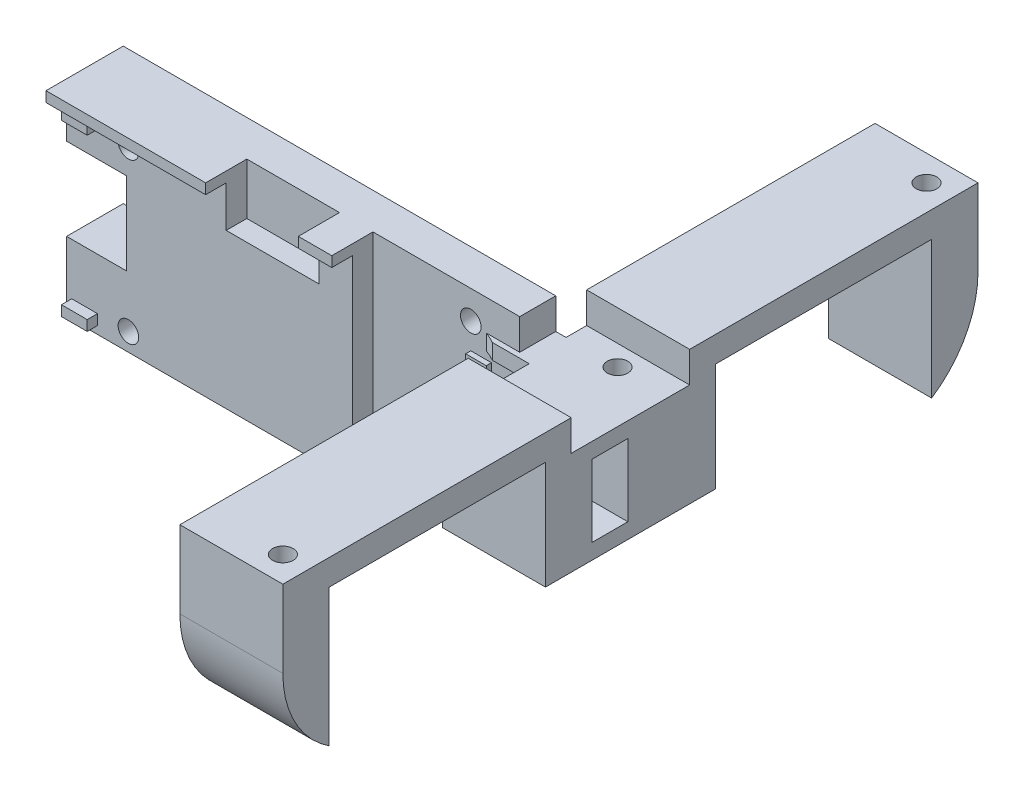
SolidWorks part; units mm, degrees
material "ABS"
ref_plane "Front Plane" through (0, 0, 0) normal (0, 0, 1) x (1, 0, 0)
ref_plane "Top Plane" through (0, 0, 0) normal (0, 1, 0) x (1, 0, 0)
ref_plane "Right Plane" through (0, 0, 0) normal (1, 0, 0) x (0, 0, -1)
sketch "Sketch1" plane through (0, 0, 0) normal (0, 1, 0) x (1, 0, 0)
  line L1 (-40.3176, 43.2333) -> (45.6824, 43.2333)
  line L2 (45.6824, 43.2333) -> (45.6824, -16.7667)
  line L3 (45.6824, -16.7667) -> (65.6824, -16.7667)
  line L4 (65.6824, -16.7667) -> (65.6824, 118.2333)
  line L7 (-40.3176, 43.2333) -> (-40.3176, 58.2333)
  line L8 (-40.3176, 58.2333) -> (45.6824, 58.2333)
  line L9 (45.6824, 58.2333) -> (45.6824, 118.2333)
  line L10 (45.6824, 118.2333) -> (65.6824, 118.2333)
  dimension "D1" = 20
  dimension "D2" = 60
  dimension "D3" = 86
  dimension "D4" = 15
  dimension "D5" = 60
  dimension "D6" = 20
extrude "Boss-Extrude1" add sketch "Sketch1" along normal blind 35
sketch "Sketch2" plane through (65.6824, 0, 0) normal (1, 0, 0) x (0, 0, -1)
  line L1 (-7.7667, 30) -> (34.2333, 30)
  line L2 (-7.7667, 30) -> (-7.7667, 9)
  line L3 (-7.7667, 9) -> (34.2333, 9)
  line L4 (34.2333, 30) -> (34.2333, 9)
  line L5 (-16.7667, 35) -> (-16.7667, 0) construction
  line L6 (50.7333, 24.6294) -> (50.7333, 59.3446) construction
  line L7 (-16.7667, 0) -> (118.2333, 0) construction
  line L9 (109.2333, 9) -> (67.2333, 9)
  line L10 (109.2333, 30) -> (109.2333, 9)
  line L11 (109.2333, 30) -> (67.2333, 30)
  line L12 (67.2333, 30) -> (67.2333, 9)
  dimension "D1" = 21
  dimension "D2" = 42
  dimension "D3" = 9
  dimension "D4" = 9
  dimension "D5" = 7.5
extrude "Cut-Extrude1" cut sketch "Sketch2" against normal up to next
sketch "Sketch3" plane through (45.6824, 0, 0) normal (-1, 0, 0) x (0, 0, 1)
  line L0 (7.7667, 9) -> (7.7667, 30) construction
  line L1 (-34.2333, 9) -> (7.7667, 9) construction
  line L2 (-50.7333, 32.1987) -> (-50.7333, 60.1119) construction
  line L3 (-43.2333, 35) -> (-43.2333, 0) construction
  circle A0 centre (11.2667, 24.75) radius 2
  circle A1 centre (11.2667, 15.25) radius 2
  circle A2 centre (-37.7333, 24.75) radius 2
  circle A3 centre (-37.7333, 15.25) radius 2
  circle A4 centre (-112.7333, 24.75) radius 2
  circle A5 centre (-112.7333, 15.25) radius 2
  circle A6 centre (-63.7333, 15.25) radius 2
  circle A7 centre (-63.7333, 24.75) radius 2
  dimension "D1" = 4
  dimension "D2" = 49
  dimension "D3" = 9.5
  dimension "D4" = 3.5
  dimension "D5" = 6.25
  dimension "D6" = 7.5
extrude "Cut-Extrude2" cut sketch "Sketch3" against normal blind 10
fillet "Fillet1" radius 20 2 edges at (55.6824, 0, 16.7667) (55.6824, 0, -118.2333)
sketch "Sketch6" plane through (65.6824, 0, 0) normal (1, 0, 0) x (0, 0, -1)
  line L0 (34.2333, 9) -> (34.2333, 30) construction
  line L1 (-7.7667, 9) -> (34.2333, 9)
  line L2 (-7.7667, 9) -> (-7.7667, 0)
  line L3 (-7.7667, 0) -> (34.2333, 0)
  line L4 (34.2333, 9) -> (34.2333, 0)
  line L5 (3.2333, 0) -> (98.2333, 0) construction
  line L6 (50.7333, 24.0053) -> (50.7333, 51.0852) construction
  line L7 (67.2333, 9) -> (67.2333, 0)
  line L8 (109.2333, 9) -> (67.2333, 9)
  line L9 (109.2333, 0) -> (67.2333, 0)
  line L10 (109.2333, 9) -> (109.2333, 0)
  dimension "D1" = 7.5
extrude "Cut-Extrude5" cut sketch "Sketch6" against normal up to next
sketch "Sketch8" plane through (0, 0, 0) normal (0, -1, 0) x (1, 0, 0)
  line L1 (45.6824, -67.2333) -> (45.6824, -58.2333) construction
  line L2 (45.6824, -67.2333) -> (65.6824, -67.2333) construction
  line L3 (65.6824, -34.2333) -> (65.6824, -67.2333) construction
  line L4 (45.6824, -34.2333) -> (65.6824, -34.2333) construction
  line L5 (45.6824, -43.2333) -> (45.6824, -34.2333) construction
  line L9 (45.6824, -67.2333) -> (45.6824, -58.2333)
  line L10 (45.6824, -67.2333) -> (65.6824, -67.2333)
  line L11 (65.6824, -34.2333) -> (65.6824, -67.2333)
  line L12 (45.6824, -34.2333) -> (65.6824, -34.2333)
  line L13 (45.6824, -43.2333) -> (45.6824, -34.2333)
  line L16 (45.6824, -43.2333) -> (25.6824, -43.2333)
  line L17 (-40.3176, -43.2333) -> (45.6824, -43.2333) construction
  line L18 (25.6824, -43.2333) -> (25.6824, -58.2333)
  line L19 (45.6824, -58.2333) -> (-40.3176, -58.2333) construction
  line L20 (25.6824, -58.2333) -> (45.6824, -58.2333)
  dimension "D1" = 20
extrude "Cut-Extrude7" cut sketch "Sketch8" against normal blind 9
sketch "Sketch9" plane through (0, 9, 0) normal (0, -1, 0) x (1, 0, 0)
  line L1 (65.6824, -34.2333) -> (45.6824, -34.2333) construction
  line L2 (65.6824, -67.2333) -> (65.6824, -34.2333) construction
  line L3 (45.6824, -67.2333) -> (65.6824, -67.2333) construction
  circle A0 centre (55.6824, -42.2333) radius 2
  circle A1 centre (55.6824, -59.2333) radius 2
  dimension "D4" = 10
  dimension "D5" = 8
  dimension "D6" = 8
extrude "Cut-Extrude8" cut sketch "Sketch9" against normal blind 10
sketch "Sketch10" plane through (0, 35, 0) normal (0, 1, 0) x (1, 0, 0)
  line L0 (45.6824, 62.2333) -> (65.6824, 62.2333)
  line L1 (45.6824, 118.2333) -> (45.6824, 58.2333) construction
  line L2 (65.6824, -16.7667) -> (65.6824, 118.2333) construction
  line L3 (65.6824, 62.2333) -> (65.6824, 39.2333)
  line L4 (65.6824, 39.2333) -> (45.6824, 39.2333)
  line L5 (45.6824, 43.2333) -> (45.6824, -16.7667) construction
  line L7 (45.6824, 39.2333) -> (45.6824, 43.2333)
  line L8 (45.6824, 43.2333) -> (43.6824, 43.2333)
  line L9 (-40.3176, 43.2333) -> (45.6824, 43.2333) construction
  line L10 (43.6824, 43.2333) -> (43.6824, 58.2333)
  line L11 (45.6824, 58.2333) -> (-40.3176, 58.2333) construction
  line L12 (43.6824, 58.2333) -> (45.6824, 58.2333)
  line L13 (45.6824, 58.2333) -> (45.6824, 62.2333)
  dimension "D1" = 5
  dimension "D2" = 5
  dimension "D3" = 2
extrude "Cut-Extrude9" cut sketch "Sketch10" against normal blind 6
sketch "Sketch11" plane through (0, 29, 0) normal (0, 1, 0) x (1, 0, 0)
  line L0 (45.6824, 62.2333) -> (45.6824, 58.2333) construction
  circle A0 centre (55.6824, 58.2333) radius 2
  circle A1 centre (55.6824, 43.2333) radius 2
  dimension "D1" = 4
  dimension "D2" = 10
  dimension "D5" = 0
extrude "Cut-Extrude10" cut sketch "Sketch11" against normal blind 9
sketch "Sketch12" plane through (0, 35, 0) normal (0, 1, 0) x (1, 0, 0)
  line L0 (65.6824, 118.2333) -> (45.6824, 118.2333) construction
  line L1 (45.6824, -16.7667) -> (65.6824, -16.7667) construction
  line L2 (65.6824, -16.7667) -> (65.6824, 39.2333) construction
  line L3 (65.6824, 62.2333) -> (65.6824, 118.2333) construction
  circle A0 centre (60.6824, -11.7667) radius 2
  circle A1 centre (60.6824, 113.2333) radius 2
  dimension "D2" = 4
  dimension "D1" = 5
  dimension "D3" = 5
  dimension "D4" = 5
  dimension "D5" = 5
extrude "Cut-Extrude11" cut sketch "Sketch12" against normal blind 10
sketch "Sketch14" plane through (0, 0, -43.2333) normal (0, 0, 1) x (1, 0, 0)
  line L0 (-40.3176, 35) -> (-40.3176, 0) construction
  line L1 (-40.3176, 33) -> (44.6824, 33)
  line L2 (-40.3176, 33) -> (-40.3176, 0)
  line L3 (-40.3176, 0) -> (44.6824, 0)
  line L4 (44.6824, 33) -> (44.6824, 0)
  line L5 (-40.3176, 0) -> (25.6824, 0) construction
  line L7 (-40.3176, 35) -> (43.6824, 35) construction
  dimension "D1" = 85
  dimension "D2" = 2
extrude "Cut-Extrude13" cut sketch "Sketch14" against normal blind 4
sketch "Sketch15" plane through (0, 0, -47.2333) normal (0, 0, 1) x (1, 0, 0)
  line L1 (15.6824, 20) -> (43.6824, 20)
  line L3 (15.6824, 0) -> (43.6824, 0)
  line L4 (43.6824, 20) -> (43.6824, 0)
  line L5 (43.6824, 29) -> (43.6824, 33) construction
  line L6 (-40.3176, 0) -> (25.6824, 0) construction
  line L13 (15.6824, 20) -> (15.6824, 0)
  line L14 (-40.3176, 33) -> (-40.3176, 0) construction
  point P0 (14.6824, 18.5247)
  point P7 (14.6824, 8)
  point P10 (18.6824, 8)
  point P11 (15.265, 8)
  dimension "D1" = 20
  dimension "D3" = 0
  dimension "D5" = 56
extrude "Cut-Extrude14" cut sketch "Sketch15" against normal blind 4
sketch "Sketch16" plane through (0, 0, 0) normal (0, -1, 0) x (1, 0, 0)
  line L0 (25.6824, -58.2333) -> (-40.3176, -58.2333) construction
  line L1 (-40.3176, -47.2333) -> (39.6824, -47.2333)
  line L2 (-40.3176, -47.2333) -> (-40.3176, -58.2333)
  line L3 (-40.3176, -58.2333) -> (39.6824, -58.2333)
  line L4 (39.6824, -47.2333) -> (39.6824, -58.2333)
  dimension "D1" = 80
extrude "Boss-Extrude2" add sketch "Sketch16" along normal blind 5 and the other way up to surface (9 mm away) other way up to face at (45.1824, 9, -50.2333)
sketch "Sketch13" plane through (0, 0, -43.2333) normal (0, 0, 1) x (1, 0, 0)
  line L1 (-38.3176, 32) -> (36.6824, 32) construction
  line L2 (-38.3176, 32) -> (-38.3176, -4) construction
  line L3 (-38.3176, -4) -> (36.6824, -4) construction
  line L4 (36.6824, 32) -> (36.6824, -4) construction
  line L5 (-40.3176, 33) -> (-40.3176, -5) construction
  line L6 (-40.3176, 35) -> (43.6824, 35) construction
  circle A0 centre (-28.3176, 29.5) radius 2
  circle A1 centre (34.1824, 29.5) radius 2
  circle A2 centre (34.1824, -1.5) radius 2
  circle A3 centre (-28.3176, -1.5) radius 2
  dimension "D3" = 4
  dimension "D1" = 31
  dimension "D2" = 62.5
  dimension "D4" = 75
  dimension "D5" = 36
  dimension "D6" = 2.5
  dimension "D7" = 10
  dimension "D8" = 2
  dimension "D9" = 5.5
extrude "Cut-Extrude12" cut sketch "Sketch13" against normal blind 12
fillet "Fillet2" radius 2 1 edges at (39.6824, -5, -52.7333)
sketch "Sketch17" plane through (0, 0, -43.2333) normal (0, 0, 1) x (1, 0, 0)
  line L1 (43.6824, -5) -> (15.1824, -5)
  line L2 (43.6824, -5) -> (43.6824, 35)
  line L4 (15.1824, -5) -> (15.1824, 35)
  line L5 (-40.3176, 35) -> (43.6824, 35) construction
  line L7 (-9.3176, 35) -> (8.6824, 35)
  line L8 (-9.3176, 35) -> (-9.3176, 25)
  line L9 (-9.3176, 25) -> (8.6824, 25)
  line L10 (8.6824, 35) -> (8.6824, 25)
  line L11 (15.1824, 35) -> (43.6824, 35)
  circle A1 centre (-28.3176, 29.5) radius 2 construction
  point P4 (0, 0)
  point P10 (0, 0)
  point P11 (43.6824, 35)
  point P17 (43.097, 35)
  dimension "D3" = 19
  dimension "D2" = 6.5
  dimension "D4" = 18
  dimension "D5" = 10
  dimension "D6" = 40
extrude "Cut-Extrude15" cut sketch "Sketch17" against normal blind 8
sketch "Sketch20" plane through (0, 0, -47.2333) normal (0, 0, 1) x (1, 0, 0)
  line L0 (-40.3176, 33) -> (-40.3176, -5) construction
  line L1 (-40.3176, 24.5) -> (-32.3176, 24.5)
  line L2 (-40.3176, 24.5) -> (-40.3176, 8.5)
  line L3 (-40.3176, 8.5) -> (-32.3176, 8.5)
  line L4 (-32.3176, 24.5) -> (-32.3176, 8.5)
  circle A0 centre (-28.3176, 29.5) radius 2 construction
  dimension "D1" = 8
  dimension "D2" = 16
  dimension "D3" = 5
extrude "Cut-Extrude18" cut sketch "Sketch20" against normal up to next
sketch "Sketch7" plane through (-40.3176, 0, 0) normal (-1, 0, 0) x (0, 0, 1)
  line L1 (-47.2333, -5) -> (-58.2333, -5) construction
  line L2 (-58.2333, 35) -> (-43.2333, 35) construction
  line L3 (-43.2333, 35) -> (-43.2333, 33) construction
  circle A0 centre (-50.7333, 28.5) radius 2
  circle A1 centre (-50.7333, 5) radius 2
  dimension "D1" = 4
  dimension "D2" = 10
  dimension "D4" = 6.5
  dimension "D5" = 7.5
extrude "Cut-Extrude6" cut sketch "Sketch7" against normal blind 13
chamfer "Chamfer1" distance 10 angle 20 1 edges at (-32.3176, 16.5, -47.2333)
sketch "Sketch21" plane through (0, 0, -47.2333) normal (0, 0, 1) x (1, 0, 0)
  line L0 (-38.3176, 32) -> (36.6824, 32) construction
  line L1 (-38.3176, 32) -> (-38.3176, -4) construction
  line L2 (-38.3176, -4) -> (36.6824, -4) construction
  line L3 (36.6824, 32) -> (36.6824, -4) construction
  line L5 (33.1824, 26.5) -> (39.1824, 26.5) construction
  line L6 (33.1824, 26.5) -> (33.1824, 14) construction
  line L7 (33.1824, 14) -> (39.1824, 14)
  line L8 (39.1824, 26.5) -> (39.1824, 14) construction
  line L9 (32.6824, 13) -> (37.6824, 13) construction
  line L10 (32.6824, 13) -> (32.6824, 3) construction
  line L11 (32.6824, 3) -> (37.6824, 3) construction
  line L12 (37.6824, 13) -> (37.6824, 3) construction
  circle A0 centre (-28.3176, 29.5) radius 2
  circle A1 centre (34.1824, 29.5) radius 2
  circle A2 centre (34.1824, -1.5) radius 2
  circle A3 centre (-28.3176, -1.5) radius 2
  dimension "D3" = 4
  dimension "D1" = 31
  dimension "D2" = 62.5
  dimension "D4" = 75
  dimension "D5" = 36
  dimension "D6" = 2.5
  dimension "D7" = 10
  dimension "D8" = 12.5
  dimension "D9" = 6
  dimension "D10" = 3.5
  dimension "D11" = 5.5
  dimension "D12" = 5
  dimension "D13" = 10
  dimension "D14" = 7
  dimension "D15" = 1
sketch "Sketch22" plane through (65.6824, 0, 0) normal (1, 0, 0) x (0, 0, -1)
  line L0 (39.2333, 29) -> (62.2333, 29) construction
  line L1 (43.2333, 26) -> (50.2333, 26)
  line L2 (43.2333, 26) -> (43.2333, 12)
  line L3 (43.2333, 12) -> (50.2333, 12)
  line L4 (50.2333, 26) -> (50.2333, 12)
  line L5 (39.2333, 29) -> (39.2333, 35) construction
  dimension "D1" = 14
  dimension "D2" = 3
  dimension "D3" = 4
  dimension "D4" = 7
extrude "Cut-Extrude19" cut sketch "Sketch22" against normal up to next
sketch "Sketch24" plane through (0, 29, 0) normal (0, 1, 0) x (1, 0, 0)
  line L0 (43.6824, 51.2333) -> (15.1824, 51.2333) construction
  line L1 (45.6824, 39.2333) -> (45.6824, -16.7667) construction
  line L2 (43.6824, 51.2333) -> (43.6824, 47.2333) construction
  line L3 (37.1824, 51.2333) -> (45.6824, 51.2333)
  line L4 (45.6824, 51.2333) -> (45.6824, 39.2333)
  arc A0 (37.1824, 51.2333) -> (45.6824, 39.2333) centre (32.9618, 39.2333) cw
  dimension "D1" = 6.5
extrude "Boss-Extrude4" add sketch "Sketch24" against normal up to surface (3 mm away) up to face at (51.6824, 26, -45.8999)
sketch "Sketch25" plane through (0, 9, 0) normal (0, -1, 0) x (1, 0, 0)
  line L0 (45.6824, -34.2333) -> (45.6824, -43.2333) construction
  line L1 (37.1824, -51.2333) -> (45.6824, -51.2333)
  line L2 (45.6824, -51.2333) -> (45.6824, -39.2333)
  arc A1 (37.1824, -51.2333) -> (45.6824, -39.2333) centre (32.9618, -39.2333) ccw
  arc A2 (45.0371, -43.2333) -> (45.6824, -39.2333) centre (32.9618, -39.2333) ccw construction
extrude "Boss-Extrude5" add sketch "Sketch25" against normal up to surface (3 mm away) up to face at (51.6824, 12, -45.7888)
sketch "Sketch26" plane through (0, 29, 0) normal (0, 1, 0) x (1, 0, 0)
  line L0 (45.2398, 42.5597) -> (43.6861, 42.5597)
  line L1 (43.6861, 42.5597) -> (44.0632, 45.4438)
  arc A0 (44.0632, 45.4438) -> (45.2398, 42.5597) centre (32.9618, 39.2333) cw
  arc A1 (44.6824, 44.1771) -> (37.1824, 51.2333) centre (32.9618, 39.2333) ccw construction
  arc A2 (45.6824, 39.2333) -> (45.0371, 43.2333) centre (32.9618, 39.2333) ccw construction
extrude "Cut-Extrude21" cut sketch "Sketch26" against normal through all
sketch "Sketch27" plane through (0, 29, 0) normal (0, 1, 0) x (1, 0, 0)
  line L0 (43.6824, 51.2333) -> (15.1824, 51.2333) construction
  line L1 (39.3503, 50.2333) -> (46.5255, 50.2333)
  line L2 (39.3503, 50.2333) -> (39.3503, 45.2333)
  line L3 (39.3503, 45.2333) -> (46.5255, 45.2333)
  line L4 (46.5255, 50.2333) -> (46.5255, 45.2333)
  arc A0 (45.6824, 39.2333) -> (37.1824, 51.2333) centre (32.9618, 39.2333) ccw construction
  dimension "D1" = 5
  dimension "D2" = 1
extrude "Cut-Extrude22" cut sketch "Sketch27" against normal up to next
sketch "Sketch28" plane through (0, 0, -47.2333) normal (0, 0, 1) x (1, 0, 0)
  line L0 (-9.3176, 33) -> (-40.3176, 33) construction
  line L1 (-39.3176, 31.5) -> (-34.3176, 31.5)
  line L2 (-39.3176, 31.5) -> (-39.3176, 29.5)
  line L3 (-39.3176, 29.5) -> (-34.3176, 29.5)
  line L4 (-34.3176, 31.5) -> (-34.3176, 29.5)
  line L5 (-39.3176, -1.5) -> (-34.3176, -1.5)
  line L6 (-39.3176, -1.5) -> (-39.3176, -3.5)
  line L7 (-39.3176, -3.5) -> (-34.3176, -3.5)
  line L8 (-34.3176, -1.5) -> (-34.3176, -3.5)
  line L9 (15.1824, -5) -> (-40.3176, -5) construction
  line L10 (-40.3176, 8.5) -> (-40.3176, -5) construction
  line L11 (-40.3176, 33) -> (-40.3176, 24.5) construction
  dimension "D1" = 2
  dimension "D2" = 2
  dimension "D3" = 5
  dimension "D4" = 5
  dimension "D5" = 1.5
  dimension "D6" = 1.5
  dimension "D7" = 1
  dimension "D8" = 1
extrude "Boss-Extrude6" add sketch "Sketch28" along normal blind 2
sketch "Sketch29" plane through (0, 0, -51.2333) normal (0, 0, 1) x (1, 0, 0)
  line L0 (43.6824, 35) -> (15.1824, 35) construction
  line L1 (34.1824, 24.5) -> (38.1824, 24.5)
  line L2 (34.1824, 24.5) -> (34.1824, 16.5)
  line L3 (34.1824, 16.5) -> (38.1824, 16.5)
  line L4 (38.1824, 24.5) -> (38.1824, 16.5)
  line L5 (15.1824, 33) -> (15.1824, -5) construction
  dimension "D1" = 4
  dimension "D2" = 8
  dimension "D3" = 19
  dimension "D4" = 10.5
extrude "Boss-Extrude7" add sketch "Sketch29" along normal blind 1
sketch "Sketch30" plane through (0, 0, -51.2333) normal (0, 0, 1) x (1, 0, 0)
  line L0 (15.1824, -5) -> (37.6824, -5) construction
  line L1 (33.6824, 11.5) -> (36.6824, 11.5)
  line L2 (33.6824, 11.5) -> (33.6824, 4.5)
  line L3 (33.6824, 4.5) -> (36.6824, 4.5)
  line L4 (36.6824, 11.5) -> (36.6824, 4.5)
  line L5 (39.6824, -3) -> (39.6824, 9) construction
  dimension "D1" = 7
  dimension "D2" = 3
  dimension "D3" = 9.5
  dimension "D4" = 3
extrude "Boss-Extrude8" add sketch "Sketch30" along normal blind 2
